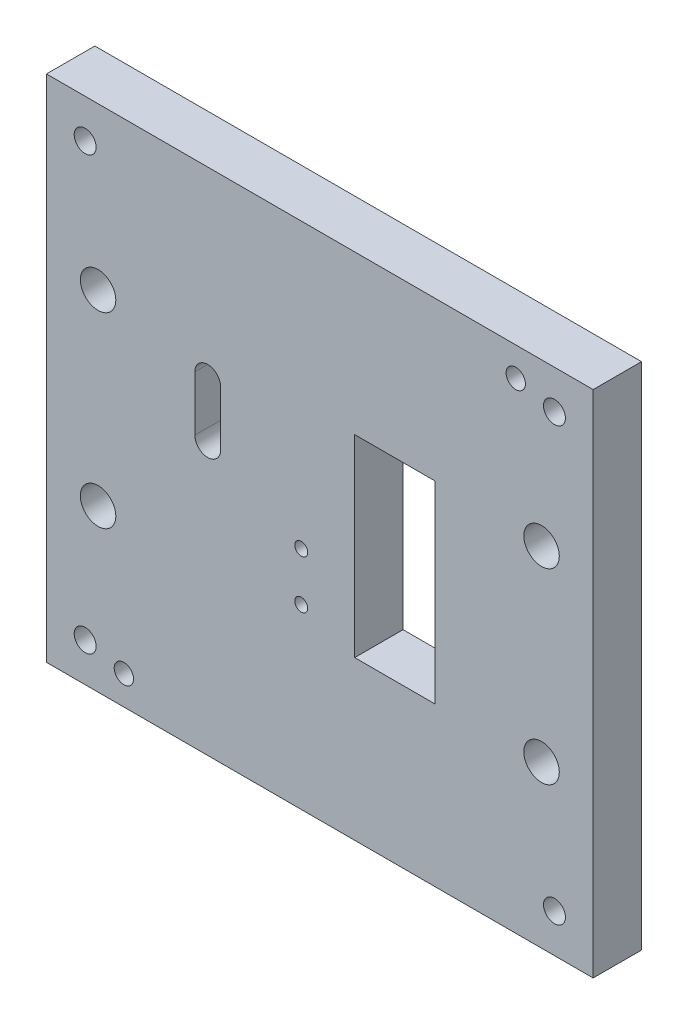
SolidWorks part; units mm, degrees
ref_plane "FP" through (0, 0, 0) normal (0, 0, 1) x (1, 0, 0)
ref_plane "TP" through (0, 0, 0) normal (0, 1, 0) x (1, 0, 0)
ref_plane "RP" through (0, 0, 0) normal (1, 0, 0) x (0, 0, -1)
sketch "Sketch2" plane through (0, 0, 0) normal (0, 0, 1) x (1, 0, 0)
  line L0 (-4, 22) -> (-4, 5) construction
  line L1 (-50, 79) -> (119.5, 79)
  line L2 (-50, 79) -> (-50, -79)
  line L3 (-50, -79) -> (119.5, -79)
  line L4 (119.5, 79) -> (119.5, -79)
  line L5 (4, 5) -> (4, 22) construction
  line L6 (-4, 22) -> (-4, 5)
  line L7 (4, 5) -> (4, 22)
  line L8 (45.56, -29.94) -> (70.44, -29.94)
  line L9 (70.44, -29.94) -> (70.44, 29.94)
  line L10 (70.44, 29.94) -> (45.56, 29.94)
  line L11 (45.56, 29.94) -> (45.56, -29.94)
  line L12 (45.56, -29.94) -> (70.44, -29.94)
  line L13 (70.44, -29.94) -> (70.44, 29.94)
  line L14 (70.44, 29.94) -> (45.56, 29.94)
  line L15 (45.56, 29.94) -> (45.56, -29.94)
  arc A4 (4, 22) -> (-4, 22) centre (0, 22) ccw construction
  arc A5 (-4, 5) -> (4, 5) centre (0, 5) ccw construction
  arc A6 (4, 22) -> (-4, 22) centre (0, 22) ccw
  arc A7 (-4, 5) -> (4, 5) centre (0, 5) ccw
  circle A8 centre (29, -9) radius 2 construction
  circle A9 centre (29, -9) radius 2
  circle A10 centre (29, -24) radius 2 construction
  circle A11 centre (29, -24) radius 2
  point P8 (-50, 79)
  point P13 (119.5, -79)
  dimension "D2" = 0
extrude "Boss-Extrude1" add sketch "Sketch2" against normal blind 15
hole_wizard "M8x1.25 Tapped Hole1" positions "Sketch3" profile "Sketch4" tap size "M8x1.25" standard "ANSI Metric"
sketch "Sketch3" plane through (0, 0, 0) normal (0, 0, 1) x (0.9063, -0.4226, 0)
  point P0 (125.7435, -15.2912)
  point P1 (69.1127, 106.1541)
  point P2 (-62.7551, 44.6631)
  point P3 (-6.1243, -76.7821)
sketch "Sketch4" plane through (107.5, -67, 0) normal (1, 0, 0) x (0, -1, 0)
  line L0 (0, 0) -> (0, 9.5429)
  line L1 (0, 9.5429) -> (3.4, 7.5)
  line L2 (3.4, 7.5) -> (3.4, 0)
  line L3 (3.4, 0) -> (0, 0)
  line L4 (0, 9.5429) -> (-3.4, 7.5) construction
  line L5 (0, -6.35) -> (0, 107.95) construction
  dimension "Tap Drill Dia." = 6.8
  dimension "Tap Drill Depth" = 7.5
  dimension "Drill Angle" = 118
cosmetic thread "Hole Thread1" parameters "D1"=6.25, "D2"=8
cosmetic thread "Hole Thread2" parameters "D1"=6.25, "D2"=8
cosmetic thread "Hole Thread3" parameters "D1"=6.25, "D2"=8
cosmetic thread "Hole Thread4" parameters "D1"=6.25, "D2"=8
hole_wizard "Ø6.0mm Clearance Dowel Hole1" positions "Sketch5" profile "Sketch6" hole size "Ø6.0" standard "ANSI Metric"
sketch "Sketch5" plane through (0, 0, 0) normal (0, 0, 1) x (0.9063, -0.4226, 0)
  point P0 (56.9691, 103.8016)
  point P1 (6.0193, -74.4296)
sketch "Sketch6" plane through (95.5, 70, 0) normal (1, 0, 0) x (0, -1, 0)
  line L0 (0, 0) -> (0, 10)
  line L1 (0, 10) -> (3, 10)
  line L2 (3, 10) -> (3, 0)
  line L5 (3, 0) -> (0, 0)
  line L11 (0, -6.35) -> (0, 107.95) construction
  dimension "Thru Hole Dia." = 6
  dimension "Thru Hole Depth" = 10
sketch "Sketch7" plane through (0, 0, -15) normal (0, 0, -1) x (-1, 0, 0)
  circle A0 centre (-103.5, 29) radius 14 construction
  circle A1 centre (34, 29) radius 14 construction
  circle A2 centre (34, -29) radius 14 construction
  circle A3 centre (-103.5, -29) radius 14 construction
  circle A4 centre (-103.5, 29) radius 14
  circle A5 centre (34, 29) radius 14
  circle A6 centre (34, -29) radius 14
  circle A7 centre (-103.5, -29) radius 14
extrude "Cut-Extrude1" cut sketch "Sketch7" against normal blind 2
hole_wizard "M10 Clearance Hole1" positions "Sketch8" profile "Sketch9" hole size "M10" standard "ANSI Metric" end condition through all
sketch "Sketch8" plane through (0, 0, 0) normal (0, 0, 1) x (0.9063, -0.4226, 0)
  point P0 (-43.0704, 11.9139)
  point P1 (-18.5585, -40.6519)
  point P2 (81.5469, 70.0239)
  point P3 (81.5469, 70.0239)
  point P4 (106.0588, 17.4581)
sketch "Sketch9" plane through (-34, 29, 0) normal (1, 0, 0) x (0, -1, 0)
  line L0 (0, 0) -> (0, 15)
  line L1 (0, 15) -> (5.5, 15)
  line L2 (5.5, 15) -> (5.5, 0)
  line L5 (5.5, 0) -> (0, 0)
  line L11 (0, -6.35) -> (0, 107.95) construction
  dimension "Thru Hole Dia." = 11
  dimension "Thru Hole Depth" = 15
